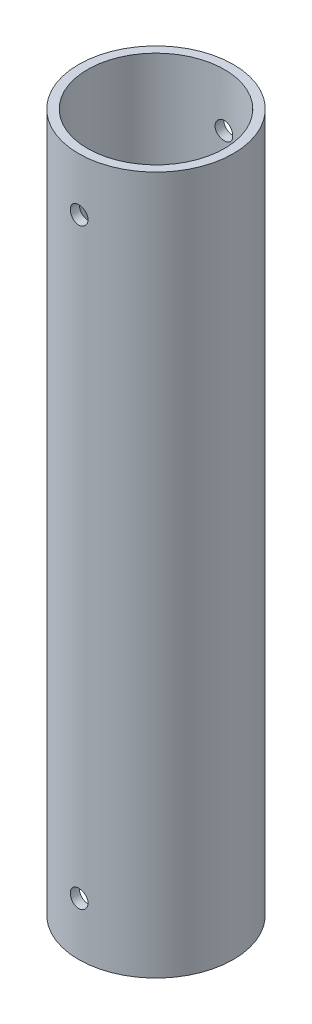
SolidWorks part; units mm, degrees
ref_plane "Plan de face" through (0, 0, 0) normal (0, 0, 1) x (1, 0, 0)
ref_plane "Plan de dessus" through (0, 0, 0) normal (0, 1, 0) x (1, 0, 0)
ref_plane "Plan de droite" through (0, 0, 0) normal (1, 0, 0) x (0, 0, -1)
sketch "Esquisse1" plane through (0, 0, 0) normal (0, 1, 0) x (1, 0, 0)
  circle A0 centre (0, 0) radius 15.5
  circle A1 centre (0, 0) radius 17.5
  dimension "D1" = 35
  dimension "D2" = 2
extrude "Boss.-Extru.1" add sketch "Esquisse1" along normal blind 158
sketch "Esquisse2" plane through (0, 0, 0) normal (0, 0, 1) x (1, 0, 0)
  line L0 (-17.5, 0) -> (17.5, 0) construction
  line L1 (17.5, 158) -> (-17.5, 158) construction
  circle A0 centre (0, 146) radius 2
  circle A1 centre (0, 12) radius 2
  dimension "D1" = 4
  dimension "D2" = 4
  dimension "D3" = 12
  dimension "D4" = 12
extrude "Enlèv. mat.-Extru.1" cut sketch "Esquisse2" against normal through all both and the other way through all
